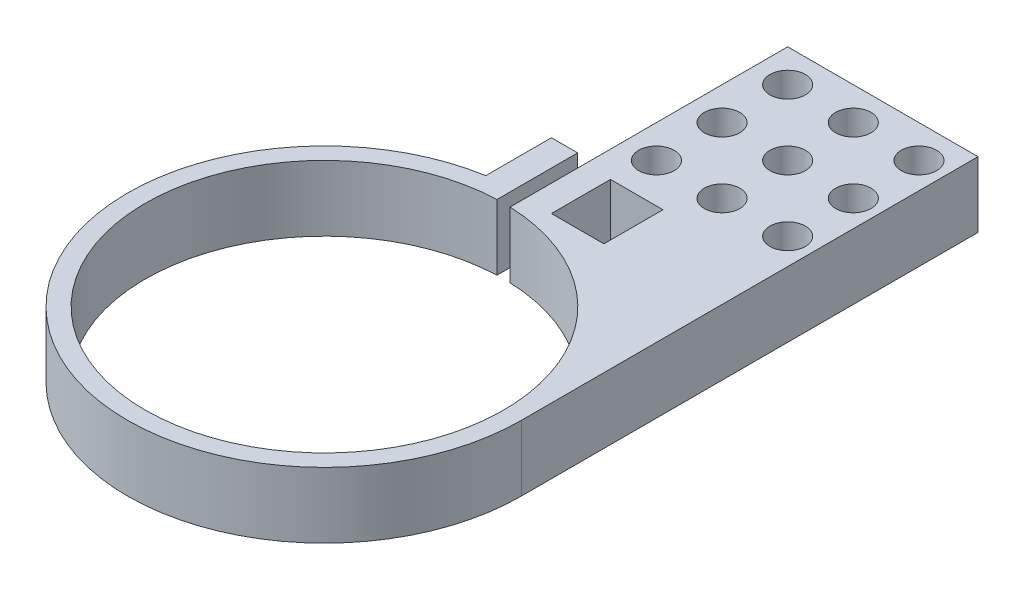
SolidWorks part; units mm, degrees
ref_plane "Front Plane" through (0, 0, 0) normal (0, 0, 1) x (1, 0, 0)
ref_plane "Top Plane" through (0, 0, 0) normal (0, 1, 0) x (1, 0, 0)
ref_plane "Right Plane" through (0, 0, 0) normal (1, 0, 0) x (0, 0, -1)
sketch "Sketch1" plane through (0, 0, 0) normal (0, 1, 0) x (1, 0, 0)
  circle A0 centre (0, 0) radius 34.671
  circle A1 centre (0, 0) radius 38.1
  dimension "D1" = 69.342
  dimension "D2" = 76.2
extrude "Boss-Extrude1" add sketch "Sketch1" along normal blind 12.7
sketch "Sketch2" plane through (0, 0, 0) normal (0, 1, 0) x (1, 0, 0)
  line L1 (6.35, 50.2671) -> (-6.35, 50.2671)
  line L2 (6.35, 50.2671) -> (6.35, 37.5671)
  line L3 (6.35, 37.5671) -> (-6.35, 37.5671)
  line L4 (-6.35, 50.2671) -> (-6.35, 37.5671)
  line L5 (6.35, 50.2671) -> (-6.35, 37.5671) construction
  line L6 (6.35, 37.5671) -> (-6.35, 50.2671) construction
  circle A0 centre (0, 0) radius 38.1 construction
  point P0 (0, 43.9171)
  dimension "D1" = 12.7
  dimension "D2" = 12.7
extrude "Boss-Extrude2" add sketch "Sketch2" along normal blind 12.7
sketch "Sketch4" plane through (0, 0, 0) normal (0, 1, 0) x (1, 0, 0)
  line L1 (-1.27, 1.4316) -> (1.27, 1.4316)
  line L2 (-1.27, 1.4316) -> (-1.27, 60.42)
  line L3 (-1.27, 60.42) -> (1.27, 60.42)
  line L4 (1.27, 1.4316) -> (1.27, 60.42)
  line L5 (-1.27, 1.4316) -> (1.27, 60.42) construction
  line L6 (-1.27, 60.42) -> (1.27, 1.4316) construction
  point P0 (0, 30.9258)
  dimension "D1" = 2.54
extrude "Cut-Extrude2" cut sketch "Sketch4" along normal through all
sketch "Sketch5" plane through (0, 0, 0) normal (1, 0, 0) x (0, 0, -1)
  line L1 (50.2671, 12.7) -> (0, 12.7)
  line L2 (50.2671, 12.7) -> (50.2671, 0)
  line L3 (50.2671, 0) -> (0, 0)
  line L4 (0, 12.7) -> (0, 0)
extrude "Boss-Extrude3" add sketch "Sketch5" against normal up to next from offset 38.1
sketch "Sketch6" plane through (0, 12.7, 0) normal (0, 1, 0) x (1, 0, 0)
  line L0 (1.27, 34.6477) -> (1.27, 50.2671) construction
  line L1 (38.1, 50.2671) -> (1.27, 50.2671)
  line L2 (38.1, 50.2671) -> (38.1, 101.0671)
  line L3 (38.1, 101.0671) -> (1.27, 101.0671)
  line L4 (1.27, 50.2671) -> (1.27, 101.0671)
  dimension "D1" = 50.8
extrude "Boss-Extrude4" add sketch "Sketch6" against normal blind 12.7
sketch "Sketch7" plane through (0, 0, 0) normal (0, 1, 0) x (1, 0, 0)
  line L0 (38.1, 101.0671) -> (1.27, 101.0671) construction
  line L2 (1.27, 34.6477) -> (1.27, 101.0671) construction
  line L4 (6.35, 48.9971) -> (16.51, 48.9971)
  line L5 (6.35, 48.9971) -> (6.35, 37.5671)
  line L6 (6.35, 37.5671) -> (16.51, 37.5671)
  line L7 (16.51, 48.9971) -> (16.51, 37.5671)
  circle A0 centre (7.62, 94.7171) radius 3.429
  circle A1 centre (20.32, 94.7171) radius 3.429
  circle A2 centre (20.32, 82.0171) radius 3.429
  circle A3 centre (7.62, 82.0171) radius 3.429
  circle A4 centre (7.62, 69.3171) radius 3.429
  circle A5 centre (20.32, 69.3171) radius 3.429
  circle A6 centre (7.62, 56.6171) radius 3.429
  circle A7 centre (20.32, 56.6171) radius 3.429
  circle A8 centre (33.02, 94.7171) radius 3.429
  circle A9 centre (33.02, 82.0171) radius 3.429
  circle A10 centre (33.02, 69.3171) radius 3.429
  circle A11 centre (33.02, 56.6171) radius 3.429
  dimension "D1" = 6.858
  dimension "D9" = 12.7
  dimension "D10" = 12.7
  dimension "D2" = 6.35
  dimension "D3" = 6.35
  dimension "D6" = 11.43
  dimension "D7" = 5.08
  dimension "D8" = 10.16
  dimension "D4" = 3
  dimension "D5" = 4
extrude "Cut-Extrude3" cut sketch "Sketch7" along normal through all
sketch "Sketch8" plane through (0, 12.7, 0) normal (0, 1, 0) x (1, 0, 0)
  line L0 (38.1, 101.0671) -> (38.1, 0) construction
  line L1 (1.27, 101.0671) -> (38.1, 101.0671)
  line L2 (1.27, 101.0671) -> (1.27, 88.3671)
  line L3 (1.27, 88.3671) -> (38.1, 88.3671)
  line L4 (38.1, 101.0671) -> (38.1, 88.3671)
  dimension "D1" = 12.7
extrude "Cut-Extrude4" cut sketch "Sketch8" against normal through all
